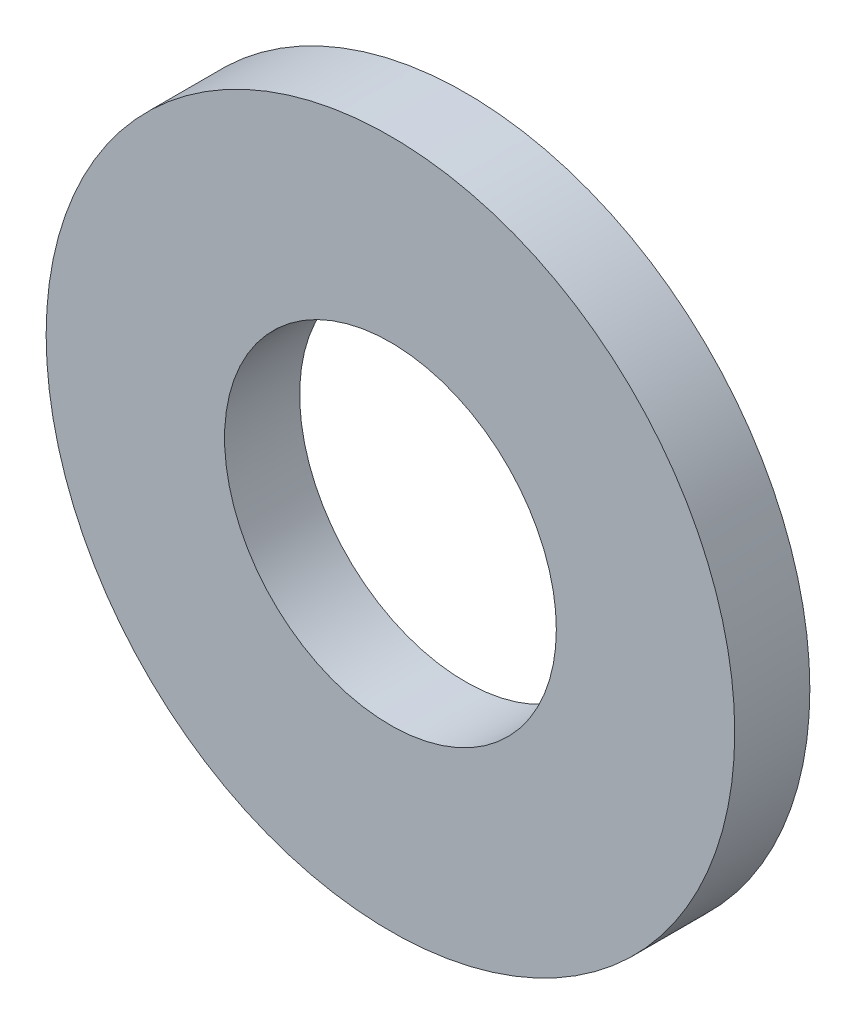
SolidWorks part; units mm, degrees
ref_plane "Front Plane" through (0, 0, 0) normal (0, 0, 1) x (1, 0, 0)
ref_plane "Top Plane" through (0, 0, 0) normal (0, 1, 0) x (1, 0, 0)
ref_plane "Right Plane" through (0, 0, 0) normal (1, 0, 0) x (0, 0, -1)
sketch "Sketch1" plane through (0, 0, 0) normal (0, 0, 1) x (1, 0, 0)
  circle A0 centre (0, 0) radius 5.5
  circle A1 centre (0, 0) radius 2.65
  dimension "OD" = 11
  dimension "ID1" = 5.3
extrude "Boss-Extrude1" add sketch "Sketch1" along normal blind 1.2
